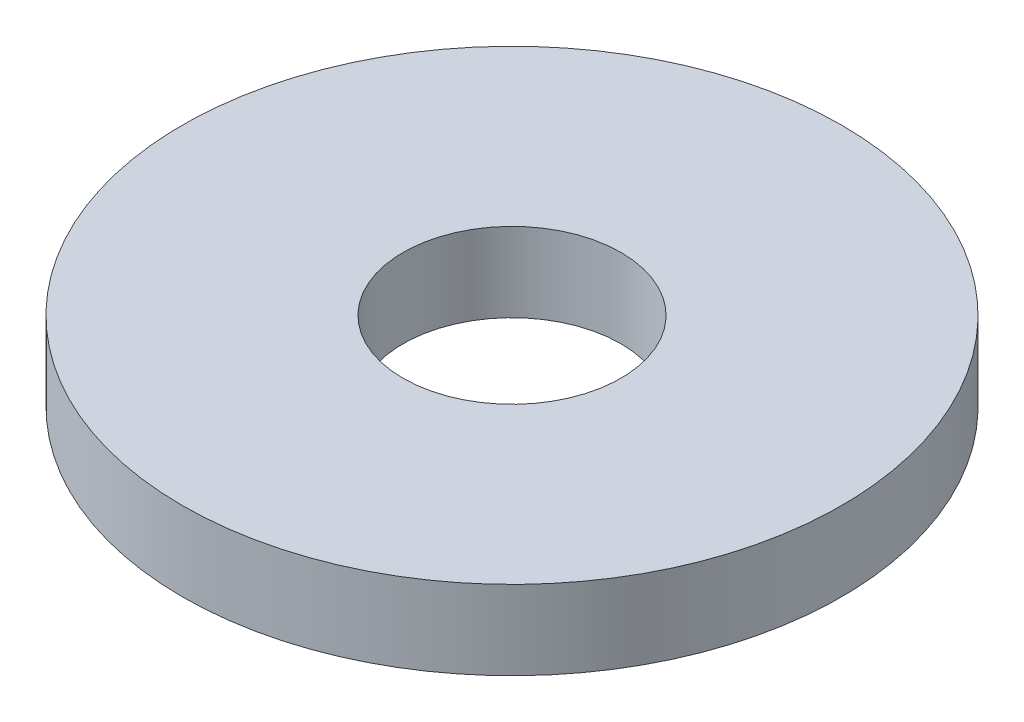
SolidWorks part; units mm, degrees
material "PTFE (general)"
ref_plane "Front Plane" through (0, 0, 0) normal (0, 0, 1) x (1, 0, 0)
ref_plane "Top Plane" through (0, 0, 0) normal (0, 1, 0) x (1, 0, 0)
ref_plane "Right Plane" through (0, 0, 0) normal (1, 0, 0) x (0, 0, -1)
sketch "Sketch1" plane through (0, 0, 0) normal (0, 1, 0) x (1, 0, 0)
  circle A0 centre (0, 0) radius 4.7625
  dimension "OD" = 9.525
extrude "Boss-Extrude1" add sketch "Sketch1" along normal blind 1.143
sketch "Sketch5" plane through (0, 1.143, 0) normal (0, 1, 0) x (-1, 0, 0)
  circle A0 centre (0, 0) radius 1.5748
  dimension "ID" = 3.1496
extrude "Cut-Extrude1" cut sketch "Sketch5" against normal through all
